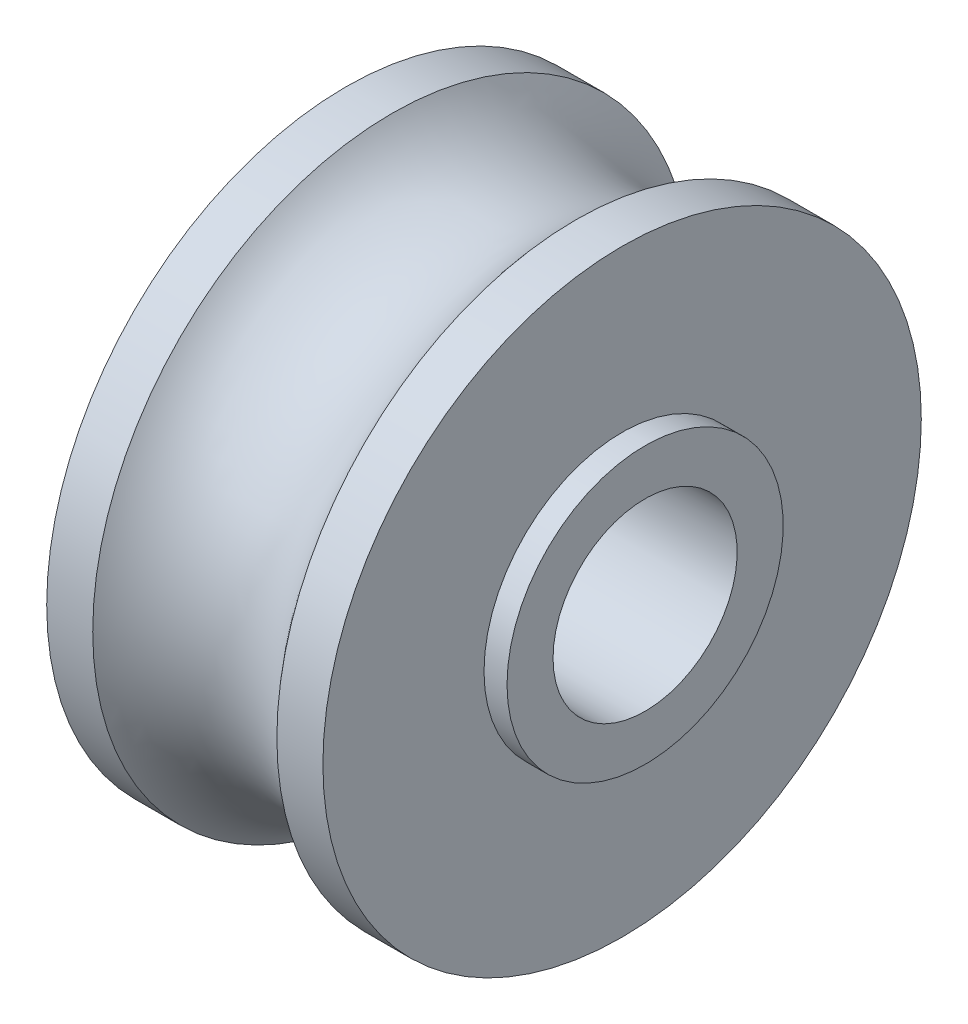
SolidWorks part; units mm, degrees
ref_plane "Plan de face" through (0, 0, 0) normal (0, 0, 1) x (1, 0, 0)
ref_plane "Plan de dessus" through (0, 0, 0) normal (0, 1, 0) x (1, 0, 0)
ref_plane "Plan de droite" through (0, 0, 0) normal (1, 0, 0) x (0, 0, -1)
sketch "Esquisse1" plane through (0, 0, 0) normal (0, 0, 1) x (1, 0, 0)
  line L0 (0, 0) -> (0, 6.5) construction
  line L1 (2, 6.5) -> (0, 6.5) construction
  line L2 (2, 6.5) -> (3, 6.5)
  line L3 (3, 6.5) -> (3, 3)
  line L6 (0, 0) -> (13.6908, 0) construction
  line L7 (-3, 6.5) -> (-3, 2)
  line L8 (-2, 6.5) -> (-3, 6.5)
  line L9 (0, 6.5) -> (0, 8) construction
  line L10 (-3, 2) -> (3.5, 2)
  line L13 (3, 3) -> (3.5, 3)
  line L14 (3.5, 2) -> (3.5, 3)
  arc A1 (-2, 6.5) -> (2, 6.5) centre (0, 8) ccw
  point P10 (0, 2)
  point P15 (0, 5.5)
  dimension "D3" = 1
  dimension "D5" = 2.5
  dimension "D1" = 6
  dimension "D2" = 6.5
  dimension "D6" = 0.5
  dimension "D7" = 1
revolve "Révolution1" add sketch "Esquisse1" angle 360 about L6
